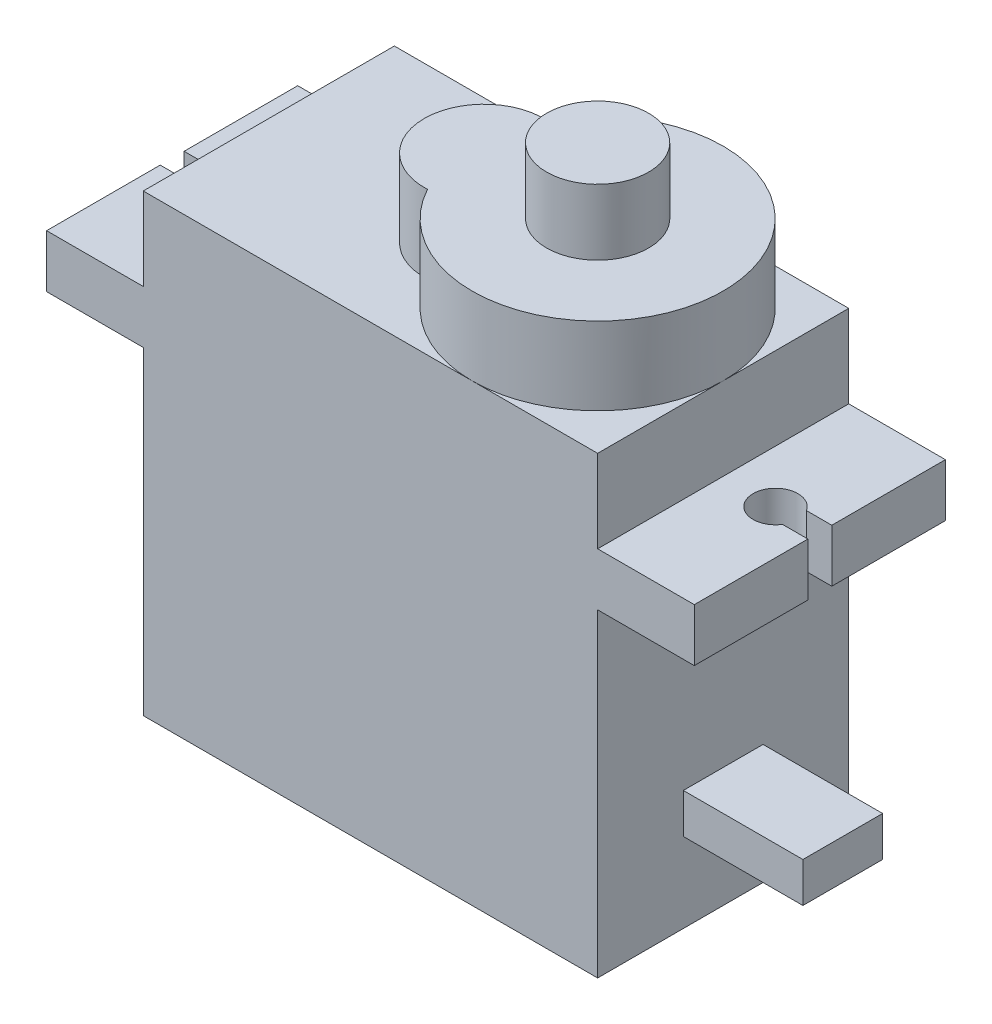
SolidWorks part; units mm, degrees
ref_plane "Front Plane" through (0, 0, 0) normal (0, 0, 1) x (1, 0, 0)
ref_plane "Top Plane" through (0, 0, 0) normal (0, 1, 0) x (1, 0, 0)
ref_plane "Right Plane" through (0, 0, 0) normal (1, 0, 0) x (0, 0, -1)
sketch "front body" plane through (0, 0, 0) normal (0, 0, 1) x (1, 0, 0)
  line L0 (-11.4, 22.8) -> (11.4, 22.8)
  line L1 (11.4, 22.8) -> (11.4, 18.65)
  line L2 (11.4, 18.65) -> (16.25, 18.65)
  line L3 (16.25, 18.65) -> (16.25, 16)
  line L4 (16.25, 16) -> (11.4, 16)
  line L5 (11.4, 16) -> (11.4, 0)
  line L6 (11.4, 0) -> (-11.4, 0)
  line L7 (0, -21.763) -> (0, 21.763) construction
  line L8 (-11.4, 16) -> (-11.4, 0)
  line L9 (-16.25, 16) -> (-11.4, 16)
  line L10 (-16.25, 18.65) -> (-16.25, 16)
  line L11 (-11.4, 18.65) -> (-16.25, 18.65)
  line L12 (-11.4, 22.8) -> (-11.4, 18.65)
  point P12 (0, 0)
  point P17 (0, 22.8)
  dimension "D1" = 22.8
  dimension "D3" = 16
  dimension "D2" = 32.5
  dimension "D4" = 22.8
  dimension "D5" = 2.65
extrude "body" add sketch "front body" along normal mid plane 12.6
sketch "Sketch2" plane through (0, 22.8, 0) normal (0, 1, 0) x (1, 0, 0)
  line L0 (11.4, 6.3) -> (-11.4, 6.3) construction
  line L1 (11.4, -6.3) -> (11.4, 6.3) construction
  line L2 (11.4, -6.3) -> (-11.4, -6.3) construction
  arc A0 (-0.4421, -2.9958) -> (-0.4421, 2.9958) centre (5.1, 0) ccw
  arc A1 (-0.4421, 2.9958) -> (-0.4421, -2.9958) centre (-0.6, 0) ccw
  point P1 (-3.6, 0)
  dimension "D1" = 6
  dimension "D2" = 15
extrude "hub body" add sketch "Sketch2" along normal blind 3.9
sketch "Sketch3" plane through (0, 26.7, 0) normal (0, 1, 0) x (1, 0, 0)
  circle A0 centre (5.1, 0) radius 2.56
  arc A1 (-0.4421, -2.9958) -> (-0.4421, 2.9958) centre (5.1, 0) ccw construction
  dimension "D1" = 5.12
extrude "hub" add sketch "Sketch3" along normal blind 30 from surface at -26.7 starting at plane "Top Plane"
sketch "mounting holes" plane through (0, 18.65, 0) normal (0, 1, 0) x (1, 0, 0)
  line L0 (-12.9, 0) -> (12.9, 0) construction
  line L2 (-14.9766, 0.6) -> (-16.25, 0.6)
  line L3 (-16.25, -6.3) -> (-16.25, 6.3) construction
  line L4 (-14.9766, -0.6) -> (-16.25, -0.6)
  line L5 (-16.25, 0.6) -> (-16.25, -0.6)
  line L6 (0, -7.48) -> (0, 7.48) construction
  line L7 (16.25, 0.6) -> (16.25, -0.6)
  line L8 (14.9766, -0.6) -> (16.25, -0.6)
  line L9 (14.9766, 0.6) -> (16.25, 0.6)
  arc A0 (-14.9766, -0.6) -> (-14.9766, 0.6) centre (-14.025, 0) ccw
  arc A2 (14.9766, -0.6) -> (14.9766, 0.6) centre (14.025, 0) cw
  point P4 (0, 0)
  dimension "D2" = 2.25
  dimension "D1" = 25.8
  dimension "D3" = 1.2
extrude "holes" cut sketch "mounting holes" against normal up to next
sketch "Sketch5" plane through (11.4, 0, 0) normal (1, 0, 0) x (0, 0, -1)
  line L0 (-6.3, 0) -> (6.3, 0) construction
  line L1 (-2, 4) -> (2, 4)
  line L2 (-2, 4) -> (-2, 6)
  line L3 (-2, 6) -> (2, 6)
  line L4 (2, 4) -> (2, 6)
  point P4 (0, 4)
  dimension "D1" = 2
  dimension "D2" = 4
  dimension "D3" = 4
extrude "Wires" add sketch "Sketch5" along normal blind 6
equation "\"D1@hub body\" = 26.7 - \"D4@front body\""
equation "\"D1@hub\" = 34.5 - \"D1@hub body\" - \"D4@front body\""
